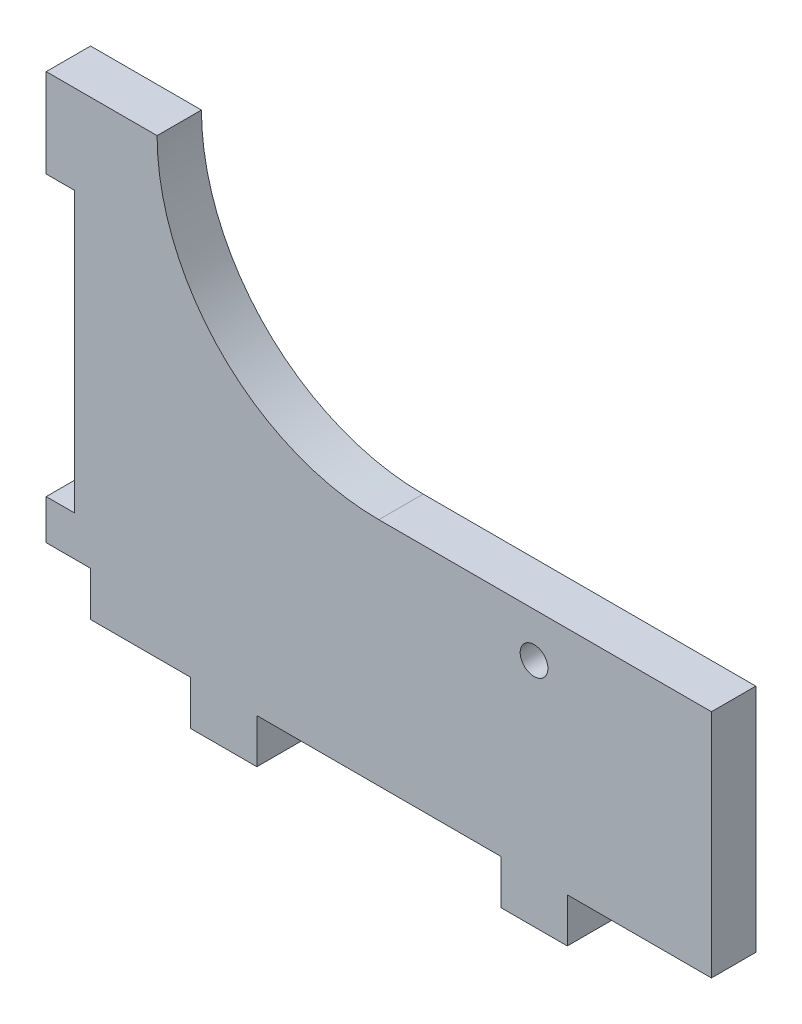
SolidWorks part; units mm, degrees
material "Acrylic (Medium-high impact)"
ref_plane "Front Plane" through (0, 0, 0) normal (0, 0, 1) x (1, 0, 0)
ref_plane "Top Plane" through (0, 0, 0) normal (0, 1, 0) x (1, 0, 0)
ref_plane "Right Plane" through (0, 0, 0) normal (1, 0, 0) x (0, 0, -1)
sketch "Sketch1" plane through (0, 0, 0) normal (0, 0, 1) x (1, 0, 0)
  line L0 (-95.25, 12.7) -> (-53.975, 12.7)
  line L1 (-53.975, 0) -> (-34.925, 0)
  line L2 (-95.25, 12.7) -> (-95.25, 142.24)
  line L3 (63.5, 142.24) -> (95.25, 142.24)
  line L4 (95.25, 12.7) -> (95.25, 142.24)
  line L5 (-34.925, 0) -> (-34.925, 12.7) construction
  line L6 (-53.975, 0) -> (-53.975, 12.7) construction
  line L7 (-34.925, 0) -> (-34.925, 12.7)
  line L8 (-53.975, 0) -> (-53.975, 12.7)
  line L9 (53.975, 0) -> (53.975, 12.7) construction
  line L10 (34.925, 0) -> (34.925, 12.7) construction
  line L11 (53.975, 0) -> (53.975, 12.7)
  line L12 (34.925, 0) -> (34.925, 12.7)
  line L13 (34.925, 0) -> (53.975, 0)
  line L14 (53.975, 12.7) -> (95.25, 12.7)
  line L15 (-34.925, 12.7) -> (34.925, 12.7)
  line L16 (-95.25, 142.24) -> (-63.5, 142.24)
  arc A0 (-63.5, 142.24) -> (63.5, 142.24) centre (0, 142.24) ccw
  dimension "D2" = 127
  dimension "D1" = 129.54
extrude "Extrude1" add sketch "Sketch1" along normal blind 12.7
sketch "Sketch2" plane through (0, 0, 12.7) normal (0, 0, 1) x (1, 0, 0)
  circle A0 centre (44.45, 66.04) radius 3.9687
  arc A1 (-63.5, 142.24) -> (63.5, 142.24) centre (0, 142.24) ccw construction
  dimension "D1" = 44.45
  dimension "D2" = 76.2
  dimension "D3" = 7.9375
extrude "Cut-Extrude1" cut sketch "Sketch2" against normal through all
sketch "Sketch3" plane through (0, 0, 12.7) normal (0, 0, 1) x (1, 0, 0)
  line L1 (-95.25, 12.7) -> (-82.55, 12.7)
  line L2 (-95.25, 12.7) -> (-95.25, 25.4)
  line L3 (-95.25, 25.4) -> (-82.55, 25.4)
  line L4 (-82.55, 12.7) -> (-82.55, 25.4)
  dimension "D1" = 12.7
extrude "Extrude2" cut sketch "Sketch3" against normal through all
sketch "Sketch4" plane through (0, 0, 12.7) normal (0, 0, 1) x (1, 0, 0)
  line L1 (0, 78.74) -> (105.9831, 78.74)
  line L2 (0, 78.74) -> (0, 153.9423)
  line L3 (0, 153.9423) -> (105.9831, 153.9423)
  line L4 (105.9831, 78.74) -> (105.9831, 153.9423)
  arc A0 (-63.5, 142.24) -> (63.5, 142.24) centre (0, 142.24) ccw construction
extrude "Extrude3" cut sketch "Sketch4" against normal through all
sketch "Croquis1" plane through (0, 0, 12.7) normal (0, 0, 1) x (1, 0, 0)
  line L0 (-95.25, 116.84) -> (-87.175, 116.84)
  line L1 (-87.175, 116.84) -> (-87.175, 36.84)
  line L2 (-87.175, 36.84) -> (-95.25, 36.84)
  line L3 (-95.25, 116.84) -> (-95.25, 36.84)
extrude "Cortar-Extruir1" cut sketch "Croquis1" against normal blind 12.7
